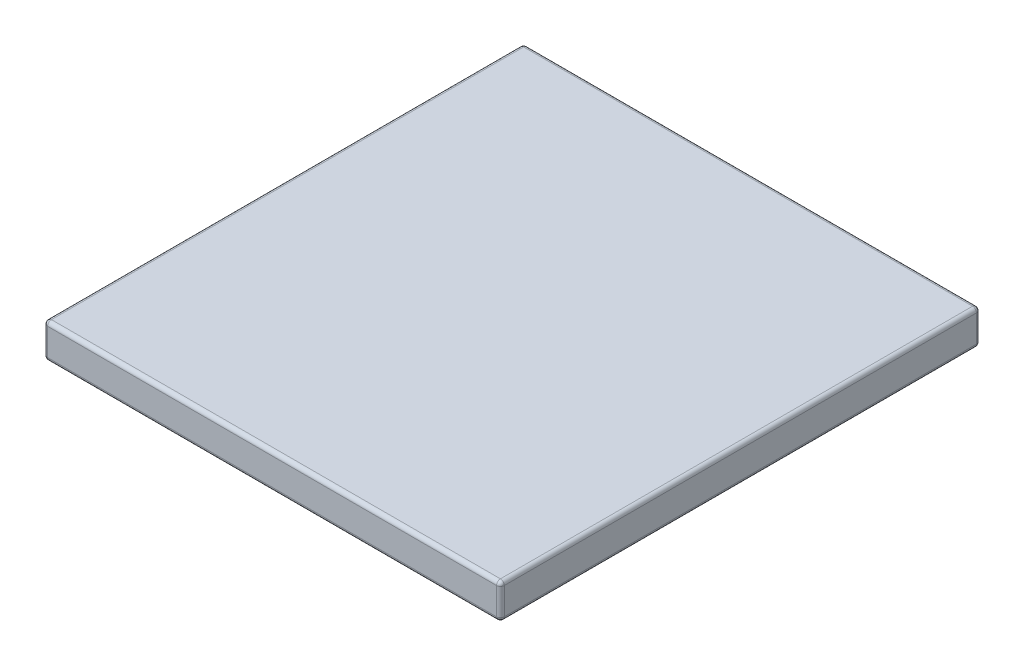
SolidWorks part; units mm, degrees
ref_plane "정면" through (0, 0, 0) normal (0, 0, 1) x (1, 0, 0)
ref_plane "윗면" through (0, 0, 0) normal (0, 1, 0) x (1, 0, 0)
ref_plane "우측면" through (0, 0, 0) normal (1, 0, 0) x (0, 0, -1)
sketch "스케치1" plane through (0, 0, 0) normal (0, 1, 0) x (1, 0, 0)
  line L0 (0, 0) -> (0, 48.2595) construction
  line L1 (-29.55, 31.05) -> (29.55, 31.05)
  line L2 (-29.55, 31.05) -> (-29.55, -31.05)
  line L3 (-29.55, -31.05) -> (29.55, -31.05)
  line L4 (29.55, 31.05) -> (29.55, -31.05)
  line L5 (0, 0) -> (63.7761, 0) construction
  dimension "D1" = 59.1
  dimension "D2" = 62.1
extrude "보스-돌출1" add sketch "스케치1" against normal blind 4.5
fillet "필렛1" radius 0.5 12 edges at (-29.55, -2.25, 31.05) (-29.55, -2.25, -31.05) (29.55, -2.25, -31.05) (29.55, -2.25, 31.05) (0, -4.5, 31.05) (29.55, -4.5, 0) (0, -4.5, -31.05) (-29.55, -4.5, 0) (0, 0, -31.05) (29.55, 0, 0) (0, 0, 31.05) (-29.55, 0, 0)
